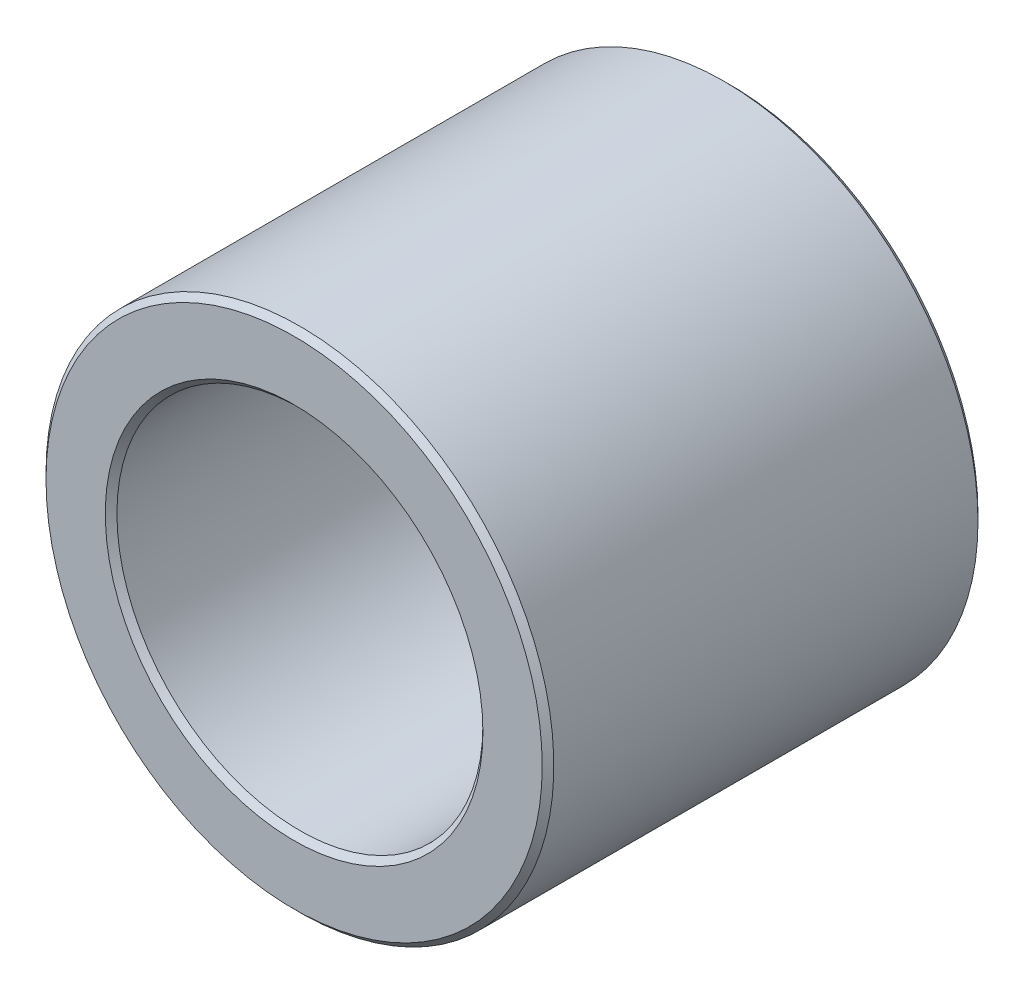
SolidWorks part; units mm, degrees
material "Hexcel AS4C (3000 Filaments)"
ref_plane "Front Plane" through (0, 0, 0) normal (0, 0, 1) x (1, 0, 0)
ref_plane "Top Plane" through (0, 0, 0) normal (0, 1, 0) x (1, 0, 0)
ref_plane "Right Plane" through (0, 0, 0) normal (1, 0, 0) x (0, 0, -1)
sketch "Sketch1" plane through (0, 0, 0) normal (0, 0, 1) x (1, 0, 0)
  circle A0 centre (0, 0) radius 5.5499
  circle A1 centre (0, 0) radius 4
  dimension "D1" = 8
  dimension "D2" = 11.0998
extrude "Boss-Extrude1" add sketch "Sketch1" along normal blind 9.525
chamfer "Chamfer1" distance 0.127 angle 45 4 edges at (4, 0, 0) (4, 0, 9.525) (5.5499, 0, 0) (5.5499, 0, 9.525)
equation "\"D1@Sketch1\"=8mm"
